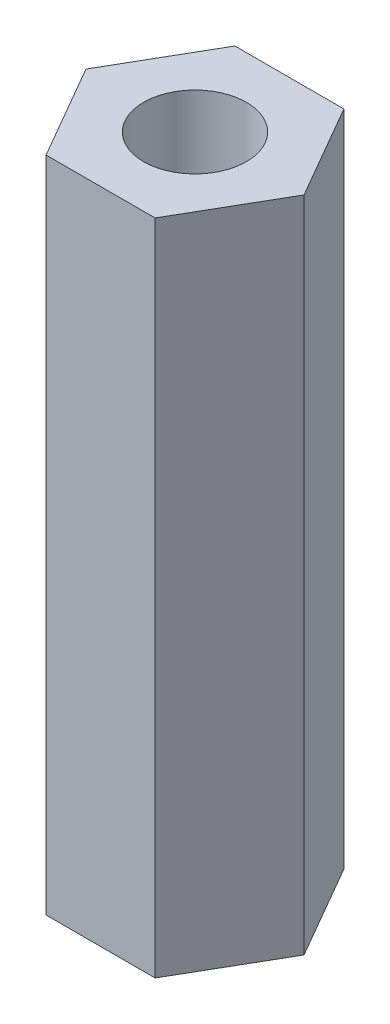
SolidWorks part; units mm, degrees
ref_plane "前视基准面" through (0, 0, 0) normal (0, 0, 1) x (1, 0, 0)
ref_plane "上视基准面" through (0, 0, 0) normal (0, 1, 0) x (1, 0, 0)
ref_plane "右视基准面" through (0, 0, 0) normal (1, 0, 0) x (0, 0, -1)
sketch "草图4" plane through (0, 0, 0) normal (0, 1, 0) x (1, 0, 0)
  line L0 (-12.7945, 0) -> (16.3015, 0) construction
  line L2 (1.325, -2.295) -> (2.65, 0)
  line L3 (2.65, 0) -> (1.325, 2.295)
  line L4 (1.325, 2.295) -> (-1.325, 2.295)
  line L5 (-1.325, 2.295) -> (-2.65, 0)
  line L6 (-2.65, 0) -> (-1.325, -2.295)
  line L7 (-1.325, -2.295) -> (1.325, -2.295)
  circle A0 centre (0, 0) radius 2.295 construction
  dimension "D1" = 5.3
extrude "凸台-拉伸1" add sketch "草图4" along normal blind 16
sketch "草图6" plane through (0, 0, 0) normal (0, -1, 0) x (-1, 0, 0)
  circle A0 centre (0, 0) radius 1.6
  dimension "D1" = 3.2
sketch "草图7" plane through (0, 16, 0) normal (0, 1, 0) x (1, 0, 0)
  circle A0 centre (0, 0) radius 1.25
  dimension "D1" = 2.5
extrude "切除-拉伸1" cut sketch "草图7" against normal blind 40
cosmetic thread "装饰螺纹线2" parameters "D2"=3
